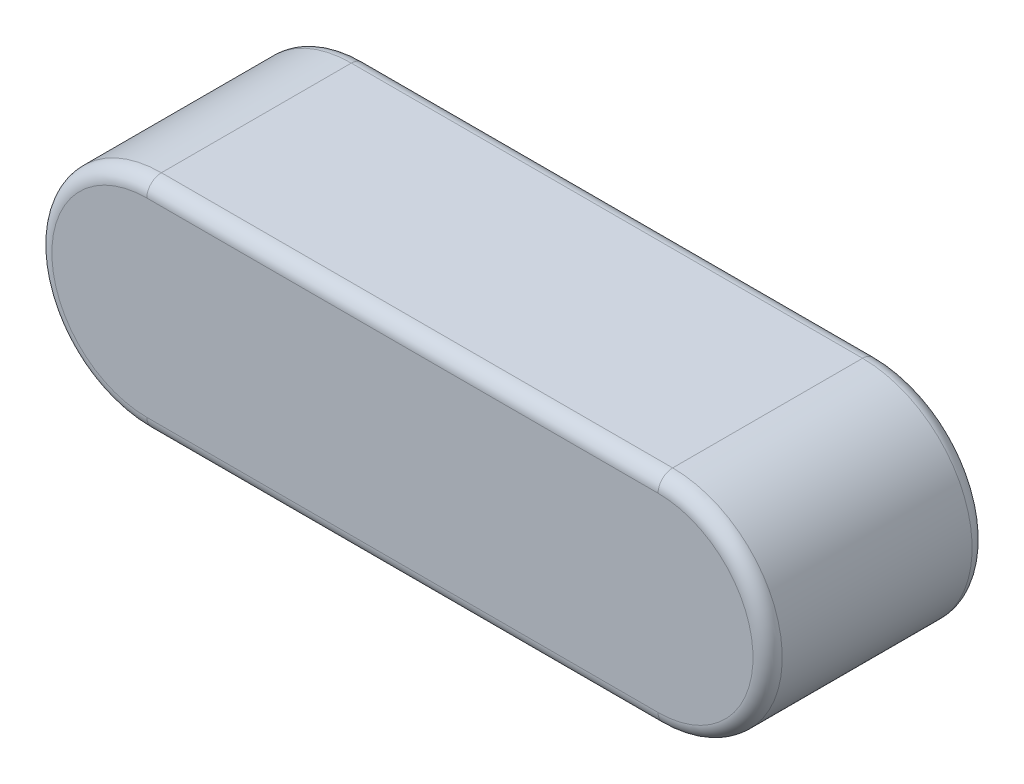
SolidWorks part; units mm, degrees
ref_plane "基准面1" through (0, 0, 0) normal (0, 0, 1) x (1, 0, 0)
ref_plane "基准面2" through (0, 0, 0) normal (0, 1, 0) x (1, 0, 0)
ref_plane "基准面3" through (0, 0, 0) normal (1, 0, 0) x (0, 0, -1)
sketch "尺寸草图" plane through (0, 0, 0) normal (0, 0, 1) x (1, 0, 0)
  line L0 (-10, 0) -> (10, 0) construction
  point P3 (-6, 0)
  point P4 (-0.4, 0)
  point P5 (0, 0)
  point P8 (-6, 0)
  point P11 (0, 0)
  dimension "L" = 20
  dimension "b" = 6
  dimension "h" = 6
  dimension "C" = 0.4
  dimension "r" = 0.4
sketch "草图1" plane through (0, 0, 0) normal (0, 0, 1) x (1, 0, 0)
  line L0 (-28.0599, 0) -> (30.562, 0) construction
  line L1 (-7, 3) -> (7, 3)
  line L2 (-7, -3) -> (7, -3)
  line L3 (0, 2.9108) -> (0, -2.1805) construction
  arc A0 (-7, 3) -> (-7, -3) centre (-7, 0) ccw
  arc A1 (7, 3) -> (7, -3) centre (7, 0) cw
  dimension "D3" = 20
  dimension "D1" = 3
extrude "基体-拉伸" add sketch "草图1" along normal blind 6
fillet "圆角1" radius 0.4 8 edges at (10, 0, 6) (0, 3, 6) (-10, 0, 6) (0, 3, 0) (10, 0, 0) (0, -3, 0) (-10, 0, 0) (0, -3, 6)
equation "\"D3@草图1\" = \"L@尺寸草图\""
equation "\"D1@草图1\" = \"b@尺寸草图\" / 2"
equation "\"D1@圆角1\" = \"r@尺寸草图\""
equation "\"D1@基体-拉伸\" = \"h@尺寸草图\""
